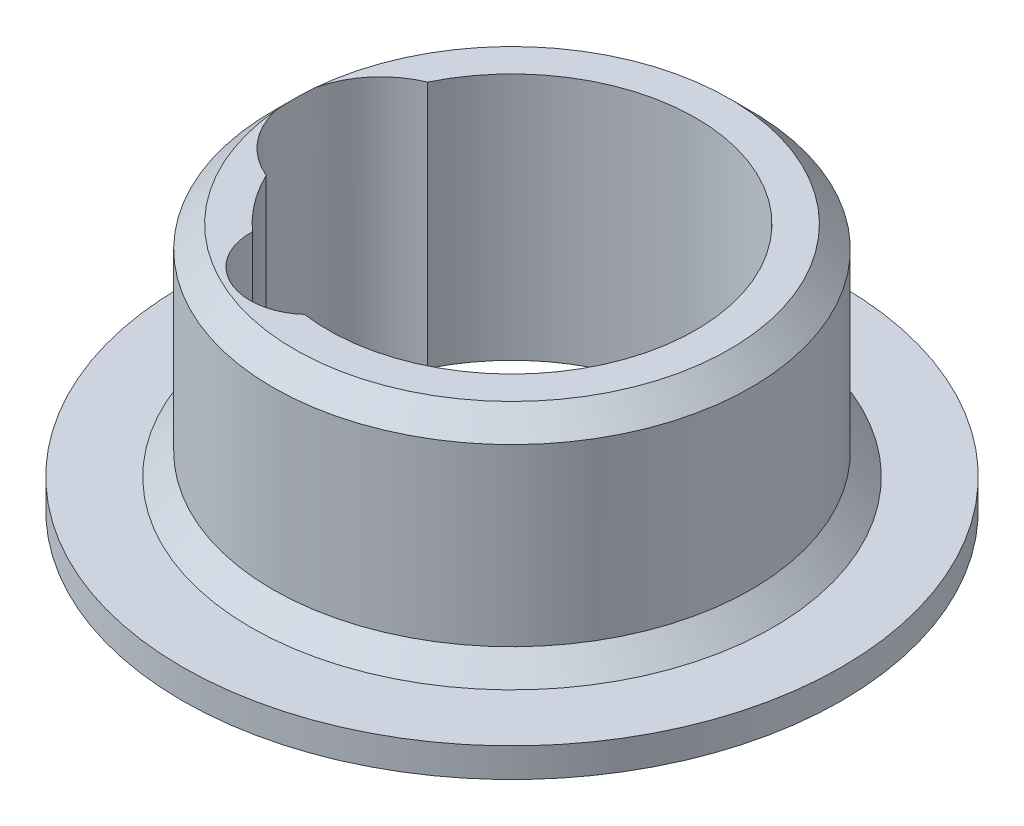
SolidWorks part; units mm, degrees
ref_plane "Plano frontal" through (0, 0, 0) normal (0, 0, 1) x (1, 0, 0)
ref_plane "Plano superior" through (0, 0, 0) normal (0, 1, 0) x (1, 0, 0)
ref_plane "Plano direito" through (0, 0, 0) normal (1, 0, 0) x (0, 0, -1)
sketch "Esboço1" plane through (0, 0, 0) normal (0, 1, 0) x (1, 0, 0)
  circle A0 centre (0, 0) radius 12.6
  circle A1 centre (0, 0) radius 22.6
  dimension "D1" = 25.2
  dimension "D2" = 10
extrude "Ressalto-extrusão1" add sketch "Esboço1" along normal blind 2
sketch "Esboço2" plane through (0, 2, 0) normal (0, 1, 0) x (1, 0, 0)
  circle A0 centre (0, 0) radius 12.6
  circle A1 centre (0, 0) radius 16.4
  dimension "D1" = 3.8
extrude "Ressalto-extrusão2" add sketch "Esboço2" along normal blind 15
chamfer "Chanfro2" distance 1.5 angle 45 2 edges at (0, 2, 16.4) (0, 17, 16.4)
sketch "Esboço3" plane through (0, 0, 0) normal (0, 1, 0) x (1, 0, 0)
  line L0 (0, 0) -> (-27.1016, 0) construction
  line L1 (0, 0) -> (-11.4194, -24.4889) construction
  line L2 (-12.6, 0) -> (-15, 0) construction
  circle A0 centre (-9, 0) radius 6
  circle A1 centre (-4.4375, -9.5162) radius 4
  circle A2 centre (0, 0) radius 12.6 construction
  dimension "D2" = 12
  dimension "D4" = 8
  dimension "D1" = 65
  dimension "D3" = 2.4
  dimension "D5" = 10.5
extrude "Corte-extrusão1" cut sketch "Esboço3" along normal through all
